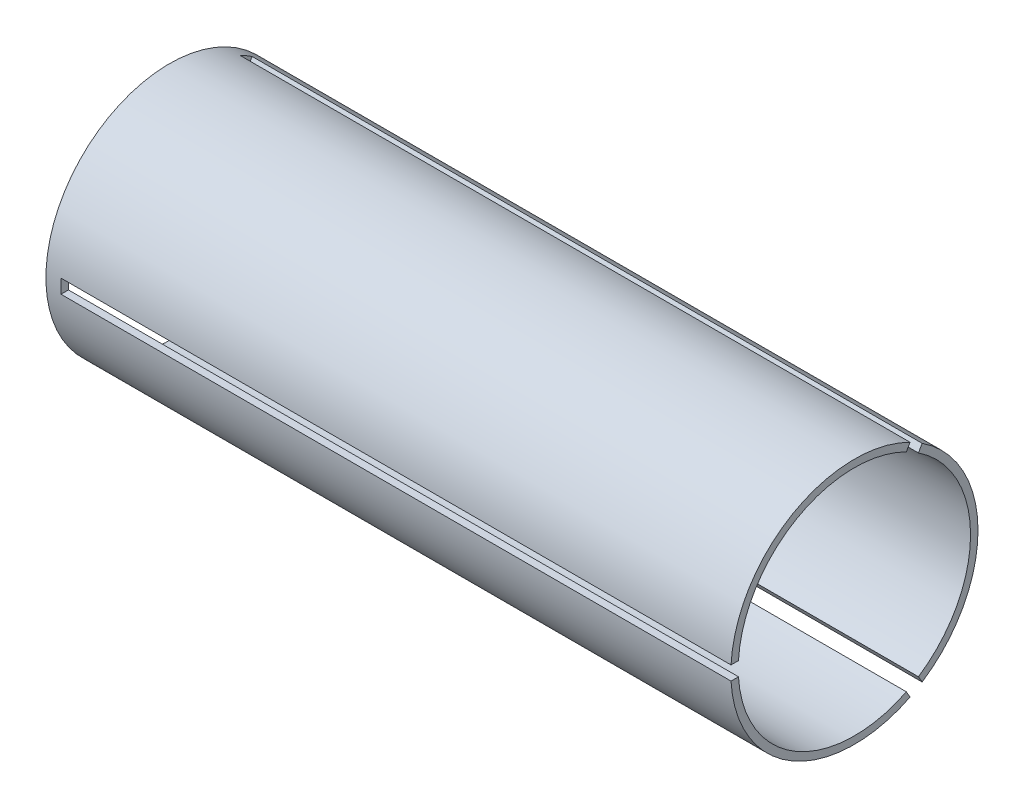
SolidWorks part; units mm, degrees
ref_plane "Front Plane" through (0, 0, 0) normal (1, 0, 0) x (0, 1, 0)
ref_plane "Top Plane" through (0, 0, 0) normal (0, 0, 1) x (0, 1, 0)
ref_plane "Right Plane" through (0, 0, 0) normal (0, 1, 0) x (-1, 0, 0)
sketch "Sketch1" plane through (0, 0, 0) normal (1, 0, 0) x (0, 1, 0)
  circle A0 centre (0, 0) radius 39.624
  circle A1 centre (0, 0) radius 42.164
  dimension "D1" = 79.248
  dimension "D2" = 2.54
extrude "Boss-Extrude1" add sketch "Sketch1" along normal blind 233.68
sketch "Sketch2" plane through (0, 0, 0) normal (0, 0, 1) x (0, 1, 0)
  line L0 (-42.164, -233.68) -> (42.164, -233.68) construction
  line L1 (-2.3813, -5.08) -> (2.3812, -5.08)
  line L2 (-2.3813, -5.08) -> (-2.3813, -233.68)
  line L3 (-2.3813, -233.68) -> (2.3812, -233.68)
  line L4 (2.3812, -5.08) -> (2.3812, -233.68)
  line L5 (-2.3813, -5.08) -> (2.3812, -233.68) construction
  line L6 (-2.3813, -233.68) -> (2.3812, -5.08) construction
  point P0 (0, -119.38)
  dimension "D1" = 4.7625
  dimension "D2" = 228.6
extrude "Cut-Extrude1" cut sketch "Sketch2" along normal through all
pattern_circular "CirPattern1" count 3 over 360 about axis through (0, 0, 0) along (1, 0, 0) of "Cut-Extrude1"
